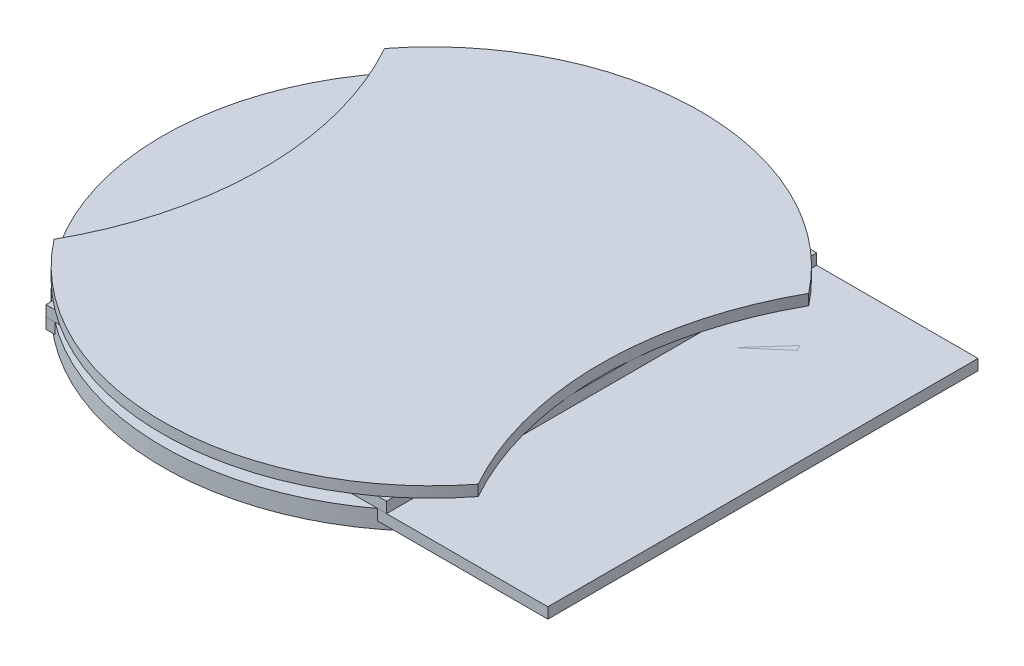
SolidWorks part; units mm, degrees
other "Markup1"
sketch "Sketch33" plane through (-11.66, 9, -138.7946) normal (0, 1, 0) x (1, 0, 0)
other "Markup2"
sketch "Sketch43" plane through (-27.5, 9, 15) normal (-0.0208, 0.9953, 0.0943) x (0.8809, -0.0263, 0.4725)
material "PMMA"
ref_plane "Front Plane" through (0, 0, 0) normal (0, 0, 1) x (1, 0, 0)
ref_plane "Top Plane" through (0, 0, 0) normal (0, 1, 0) x (1, 0, 0)
ref_plane "Right Plane" through (0, 0, 0) normal (1, 0, 0) x (0, 0, -1)
sketch "Sketch1" plane through (0, 0, 0) normal (0, 1, 0) x (1, 0, 0)
  line L1 (0, 0) -> (140, 0)
  line L2 (0, 0) -> (0, 120)
  line L3 (0, 120) -> (140, 120)
  line L4 (140, 0) -> (140, 120)
  dimension "D1" = 120
  dimension "D2" = 140
extrude "Compact" add sketch "Sketch1" along normal blind 3
sketch "Center Guide" plane through (0, 0, 0) normal (-1, 0, 0) x (0, 0, 1)
  line L0 (-60, 0) -> (-60, -3) construction
  line L1 (-120, 0) -> (0, 0) construction
  line L2 (-60, 3) -> (-60, 16.3)
  line L3 (-120, 3) -> (0, 3) construction
  line L4 (-60, 3) -> (-60, 24.5)
  circle A0 centre (-60, -3) radius 10.0584
  circle A1 centre (-60, 16.3) radius 5.9898
  circle A2 centre (-60, 24.5) radius 8.3651
  dimension "D2" = 13.3
  dimension "D3" = 21.5
  dimension "D1" = 3
sketch "Sketch4" plane through (0, 3, 0) normal (0, 1, 0) x (1, 0, 0)
  line L0 (0, 0) -> (140, 0) construction
  line L1 (0, 120) -> (95, 120)
  line L2 (0, 120) -> (0, 0)
  line L3 (0, 0) -> (95, 0)
  line L4 (95, 120) -> (95, 0)
  dimension "D1" = 95
extrude "SuperCompact" add sketch "Sketch4" along normal blind 3 separate body
sketch "Sketch5" plane through (0, 6, 0) normal (0, 1, 0) x (1, 0, 0)
  line L0 (47.5, 120) -> (47.5, 103.0921) construction
  line L1 (95, 120) -> (0, 120) construction
  line L2 (0, 60) -> (21.8037, 60) construction
  line L3 (0, 120) -> (0, 0) construction
  line L4 (70, 120) -> (70, 93.0513) construction
  line L5 (140, 120) -> (0, 120) construction
  circle A0 centre (5, 115) radius 1.5
  circle A1 centre (90, 115) radius 1.5
  circle A2 centre (90, 5) radius 1.5
  circle A3 centre (5, 5) radius 1.5
  circle A4 centre (135, 5) radius 1.5
  circle A5 centre (135, 115) radius 1.5
  dimension "D1" = 3
  dimension "D2" = 5
  dimension "D3" = 5
sketch "Sketch7" plane through (0, 6, 0) normal (0, 1, 0) x (1, 0, 0)
  line L0 (47.5, 120) -> (47.5, 0) construction
  line L1 (95, 120) -> (0, 120) construction
  line L2 (0, 0) -> (95, 0) construction
  circle A0 centre (47.5, 60) radius 75
  dimension "D1" = 150
extrude "Apple Base" add sketch "Sketch7" along normal blind 3 separate body
sketch "Sketch8" plane through (0, 9, 0) normal (0, 1, 0) x (1, 0, 0)
  line L1 (0, 120) -> (0, 0) construction
  line L2 (0, 100.6202) -> (0, 77.7186) construction
  line L3 (47.5, 135) -> (47.5, 108.0988) construction
  line L7 (-27.5, 60) -> (-27.5, 91.6393) construction
  arc A1 (-11.66, 106.0987) -> (-11.66, 13.9013) centre (-94.1268, 60) cw
  circle A2 centre (47.5, 60) radius 75 construction
  circle A3 centre (47.5, 60) radius 75
  arc A4 (-11.66, 106.0987) -> (-11.66, 13.9013) centre (47.5, 60) ccw
  arc A5 (106.66, 106.0987) -> (106.66, 13.9013) centre (189.1268, 60) ccw
  arc A6 (106.66, 106.0987) -> (106.66, 13.9013) centre (47.5, 60) cw
  dimension "D2" = 0
extrude "SideCuts" cut sketch "Sketch8" against normal through all
sketch "Sketch9" plane through (0, 6, 0) normal (0, -1, 0) x (1, 0, 0)
  arc A4 (106.66, -13.9013) -> (-11.66, -13.9013) centre (47.5, -60) ccw
  arc A5 (-11.66, -106.0987) -> (-11.66, -13.9013) centre (-94.1268, -60) ccw
  arc A6 (-11.66, -106.0987) -> (106.66, -106.0987) centre (47.5, -60) ccw
  arc A7 (106.66, -13.9013) -> (106.66, -106.0987) centre (189.1268, -60) ccw
  arc A8 (106.66, -13.9013) -> (-11.66, -13.9013) centre (47.5, -60) ccw
  arc A9 (-11.66, -106.0987) -> (-11.66, -13.9013) centre (-94.1268, -60) ccw
  arc A10 (-11.66, -106.0987) -> (106.66, -106.0987) centre (47.5, -60) ccw
  arc A11 (106.66, -13.9013) -> (106.66, -106.0987) centre (189.1268, -60) ccw
  dimension "D1" = 0
extrude "Apple_Base" add sketch "Sketch9" along normal blind 3 separate body
sketch "Sketch10" plane through (0, 6, 0) normal (0, 1, 0) x (1, 0, 0)
  line L0 (-11.66, 106.0987) -> (-11.66, 13.9013)
  line L1 (106.66, 106.0987) -> (106.66, 13.9013)
  arc A4 (106.66, 106.0987) -> (106.66, 13.9013) centre (189.1268, 60) ccw
  arc A5 (106.66, 106.0987) -> (-11.66, 106.0987) centre (47.5, 60) ccw
  arc A6 (-11.66, 13.9013) -> (-11.66, 106.0987) centre (-94.1268, 60) ccw
  arc A7 (-11.66, 13.9013) -> (106.66, 13.9013) centre (47.5, 60) ccw
  arc A8 (106.66, 106.0987) -> (106.66, 13.9013) centre (189.1268, 60) ccw
  arc A10 (-11.66, 13.9013) -> (-11.66, 106.0987) centre (-94.1268, 60) ccw
  dimension "D1" = 0
extrude "Boss-Extrude4" add sketch "Sketch10" against normal blind 3
sketch "Sketch11" plane through (0, 0, 0) normal (0, 0, 1) x (1, 0, 0)
  line L0 (-11.66, 6) -> (106.66, 6)
  line L1 (47.5, 6) -> (47.5, 18.0317)
fillet "Base_Plate_Fillet" radius 0.001 12 edges at (106.66, 6, -60) (106.66, 3, -60) (-11.66, 6, -60) (-11.66, 3, -60) (47.5, 6, -135) (47.5, 3, -135) (47.5, 6, 15) (47.5, 3, 15) (106.66, 4.5, -106.0987) (-11.66, 4.5, -106.0987) (-11.66, 4.5, -13.9013) (106.66, 4.5, -13.9013)
sketch "Sketch12" plane through (0, 6, 0) normal (0, 1, 0) x (1, 0, 0)
  line L0 (-11.659, 106.0984) -> (-11.659, 13.9016) construction
  line L1 (106.659, 13.9016) -> (106.659, 106.0984) construction
  line L2 (-4.6496, 43.9016) -> (-4.6496, 76.9016) construction
  line L3 (47.5, 134.999) -> (47.5, 105.9694) construction
  circle A0 centre (-4.6496, 43.9016) radius 2.5
  circle A1 centre (-4.6496, 76.9016) radius 2.5
  arc A2 (106.659, 106.0984) -> (-11.659, 106.0984) centre (47.5, 60) ccw construction
  circle A6 centre (99.659, 75.8016) radius 2.5
  circle A7 centre (99.659, 42.8016) radius 2.5
  dimension "D3" = 5
  dimension "D5" = 5
  dimension "D1" = 30
  dimension "D2" = 7.0094
  dimension "D4" = 33
  dimension "D6" = 33
  dimension "D7" = 28.9
  dimension "D8" = 7
extrude "Base_Screw_Holes" [suppressed] cut sketch "Sketch12" against normal blind 14
sketch "Old_Motor_Mounts" plane through (0, 6, 0) normal (0, 1, 0) x (1, 0, 0)
  line L0 (3.341, 134.7458) -> (3.341, -10.3072) construction
  line L1 (47.5, 134.999) -> (47.5, -14.999) construction
  line L2 (-11.659, 106.0984) -> (-11.659, 13.9016) construction
  line L3 (7.341, 70.6984) -> (7.341, 106.6984)
  line L4 (3.341, 70.6984) -> (3.341, 106.6984)
  line L5 (3.341, 106.6984) -> (7.341, 106.6984)
  line L6 (3.341, 70.6984) -> (7.341, 70.6984)
  line L11 (47.5, 60) -> (73.1154, 60) construction
  line L12 (91.659, 49.3016) -> (87.16, 49.4734)
  line L13 (87.16, 49.4734) -> (87.6619, 13.4542)
  line L14 (91.659, 13.3016) -> (87.6619, 13.4542)
  line L15 (91.659, 49.3016) -> (91.659, 13.3016)
  line L16 (106.659, 13.9016) -> (106.659, 106.0984) construction
  arc A0 (106.659, 106.0984) -> (-11.659, 106.0984) centre (47.5, 60) ccw construction
  arc A1 (-11.659, 13.9016) -> (106.659, 13.9016) centre (47.5, 60) ccw construction
  point P12 (3.341, 88.6984)
  point P16 (91.659, 31.3016)
  dimension "D1" = 15
  dimension "D2" = 17.4
  dimension "D3" = 36
  dimension "D5" = 36
  dimension "D6" = 15
  dimension "D7" = 4
  dimension "D8" = 17.4
  dimension "D4" = 4
ref_plane "MidPlane" through (0, 0, -60) normal (0, 0, 1) x (1, 0, 0)
sketch "Sketch24" plane through (0, 6, 0) normal (0, 1, 0) x (1, 0, 0)
  line L0 (-3.66, 114.8421) -> (-3.66, 5.1579)
  line L2 (-11.66, 13.9016) -> (-11.66, 106.0984) construction
  line L3 (47.5, 134.999) -> (47.5, 105.1076) construction
  line L4 (98.66, 114.8421) -> (98.66, 5.1579)
  line L5 (106.66, 106.0984) -> (106.66, 13.9016) construction
  line L6 (106.66, 106.0984) -> (106.66, 13.9016)
  line L7 (-11.66, 13.9016) -> (-11.66, 106.0984)
  arc A0 (106.659, 106.0984) -> (-11.659, 106.0984) centre (47.5, 60) ccw construction
  arc A1 (-11.6598, 106.099) -> (-11.66, 106.0984) centre (-11.659, 106.0984) ccw construction
  arc A2 (106.6598, 106.099) -> (-11.6598, 106.099) centre (47.5, 60) ccw construction
  arc A3 (106.66, 106.0984) -> (106.6598, 106.099) centre (106.659, 106.0984) ccw construction
  arc A4 (106.6598, 13.901) -> (106.66, 13.9016) centre (106.659, 13.9016) ccw construction
  arc A5 (-11.6598, 13.901) -> (106.6598, 13.901) centre (47.5, 60) ccw construction
  arc A6 (-11.66, 13.9016) -> (-11.6598, 13.901) centre (-11.659, 13.9016) ccw construction
  arc A7 (-11.6598, 106.099) -> (-11.66, 106.0984) centre (-11.659, 106.0984) ccw
  arc A8 (106.6598, 106.099) -> (98.66, 114.8421) centre (47.5, 60) ccw
  arc A9 (106.66, 106.0984) -> (106.6598, 106.099) centre (106.659, 106.0984) ccw
  arc A10 (106.6598, 13.901) -> (106.66, 13.9016) centre (106.659, 13.9016) ccw
  arc A11 (-11.6598, 13.901) -> (-3.66, 5.1579) centre (47.5, 60) ccw
  arc A12 (-11.66, 13.9016) -> (-11.6598, 13.901) centre (-11.659, 13.9016) ccw
  arc A13 (98.66, 5.1579) -> (106.6598, 13.901) centre (47.5, 60) ccw
  arc A14 (-3.66, 114.8421) -> (-11.6598, 106.099) centre (47.5, 60) ccw
  dimension "D1" = 8
  dimension "D2" = 8
extrude "Cut-Extrude3" [suppressed] cut sketch "Sketch24" against normal blind 6
sketch "Sketch25" plane through (0, 6, 0) normal (0, 1, 0) x (1, 0, 0)
  line L0 (-11.659, 106.0974) -> (-11.659, 111.0974)
  line L1 (47.5, 135) -> (47.5, 124.3332) construction
  line L2 (106.659, 106.0974) -> (106.659, 111.0974)
  line L3 (-11.66, 60) -> (55.4784, 60) construction
  line L4 (-11.66, 13.9016) -> (-11.66, 106.0984) construction
  line L5 (106.659, 13.9026) -> (106.659, 8.9026)
  line L6 (-11.659, 13.9026) -> (-11.659, 8.9026)
  arc A0 (-11.6598, 106.099) -> (-11.66, 106.0984) centre (-11.659, 106.0984) ccw construction
  arc A1 (106.6598, 106.099) -> (-11.6598, 106.099) centre (47.5, 60) ccw construction
  arc A2 (-11.659, 111.0974) -> (106.659, 111.0974) centre (47.5, 61.7666) cw
  arc A3 (-11.659, 106.0974) -> (106.659, 106.0974) centre (47.5, 56.7666) cw
  arc A4 (-11.659, 13.9026) -> (106.659, 13.9026) centre (47.5, 63.2334) ccw
  arc A5 (-11.659, 8.9026) -> (106.659, 8.9026) centre (47.5, 58.2334) ccw
  arc M15 (106.659, 106.0984) -> (-11.659, 106.0984) centre (47.5, 60) ccw
  arc M17 (-11.659, 13.9016) -> (106.659, 13.9016) centre (47.5, 60) ccw
  dimension "D1" = 5
extrude "Top Bottom extensions" add sketch "Sketch25" against normal blind 3 contours L6 A5 L5 A4 M17 | L0 A3 L2 A2 M15
sketch "Sketch28" plane through (0, 6, 0) normal (0, 1, 0) x (1, 0, 0)
  line L0 (-11.659, 60) -> (106.659, 60) construction
  line L1 (37.5, 6) -> (57.5, 6) construction
  line L2 (37.5, 6) -> (37.5, -14) construction
  line L3 (37.5, -14) -> (57.5, -14) construction
  line L4 (57.5, 6) -> (57.5, -14) construction
  line L5 (-11.659, 106.0984) -> (-11.659, 13.9016) construction
  line L6 (106.659, 13.9016) -> (106.659, 106.0984) construction
  line L7 (47.5, 6) -> (47.5, -4) construction
  line L8 (47.5, -4) -> (37.5, -4) construction
  circle A0 centre (41.5, 2) radius 1.75
  circle A1 centre (41.5, -10) radius 1.75
  circle A2 centre (53.5, -10) radius 1.75
  circle A3 centre (53.5, 2) radius 1.75
  circle A4 centre (53.5, 130) radius 1.75
  circle A5 centre (53.5, 118) radius 1.75
  circle A6 centre (41.5, 118) radius 1.75
  circle A7 centre (41.5, 130) radius 1.75
  point P30 (47.5, 60)
  dimension "D4" = 3.5
  dimension "D1" = 20
  dimension "D2" = 20
  dimension "D3" = 54
  dimension "D5" = 4
  dimension "D6" = 4
extrude "RodHolder holes" [suppressed] cut sketch "Sketch28" against normal blind 11
sketch "Sketch29" plane through (0, 6, 0) normal (0, 1, 0) x (1, 0, 0)
  line L0 (47.5, 138.7946) -> (47.5, -18.7946) construction
  line L5 (47.5, 60) -> (59.8359, 60) construction
  line L7 (11.25, 7.85) -> (83.75, 7.85) construction
  line L8 (11.25, 7.85) -> (11.25, 112.15) construction
  line L9 (11.25, 112.15) -> (83.75, 112.15) construction
  line L10 (83.75, 7.85) -> (83.75, 112.15) construction
  line L11 (11.25, 7.85) -> (83.75, 112.15) construction
  line L12 (11.25, 112.15) -> (83.75, 7.85) construction
  arc A5 (106.659, 111.0974) -> (-11.659, 111.0974) centre (47.5, 61.7666) ccw construction
  arc A6 (-11.659, 8.9026) -> (106.659, 8.9026) centre (47.5, 58.2334) ccw construction
  circle A7 centre (11.25, 112.15) radius 1.5
  circle A8 centre (83.75, 112.15) radius 1.5
  circle A9 centre (83.75, 7.85) radius 1.5
  circle A10 centre (11.25, 7.85) radius 1.5
  point P9 (47.5, 60)
  dimension "D1" = 104.3
  dimension "D3" = 3
  dimension "D2" = 72.5
extrude "Height extender holes" [suppressed] cut sketch "Sketch29" against normal blind 10
sketch "Sketch31" plane through (0, 6, 0) normal (0, 1, 0) x (1, 0, 0)
  line L0 (-11.659, 60) -> (106.659, 60) construction
  line L1 (-11.659, 106.0984) -> (-11.659, 13.9016) construction
  line L2 (106.659, 13.9016) -> (106.659, 106.0984) construction
  line L3 (47.5, 138.7946) -> (47.5, -18.7946) construction
  line L4 (47.5, 112) -> (72.8768, 112) construction
  arc A0 (106.659, 111.0974) -> (-11.659, 111.0974) centre (47.5, 61.7666) ccw construction
  arc A1 (-11.659, 8.9026) -> (106.659, 8.9026) centre (47.5, 58.2334) ccw construction
  circle A2 centre (47.5, 122) radius 10
  circle A3 centre (47.5, 122) radius 8
  circle A4 centre (47.5, 122) radius 15
  dimension "D1" = 20
  dimension "D3" = 2
  dimension "D4" = 30
  dimension "D2" = 52
sketch "Sketch34" plane through (0, 3, 0) normal (0, -1, 0) x (-1, 0, 0)
  line L0 (-47.5, -18.7946) -> (-47.5, 138.7946) construction
  arc A0 (-106.659, 8.9026) -> (11.659, 8.9026) centre (-47.5, 58.2334) ccw construction
  arc A1 (11.659, 111.0974) -> (-106.659, 111.0974) centre (-47.5, 61.7666) ccw construction
  circle A2 centre (-47.5, 60) radius 12.859
sketch "Sketch35" plane through (0, 3, 0) normal (0, -1, 0) x (1, 0, 0)
  line L0 (47.5, 18.7946) -> (47.5, -138.7946) construction
  line L1 (6.25, -114.85) -> (88.75, -114.85) construction
  line L2 (47.5, -60) -> (61.5955, -60) construction
  line L3 (7.5, -3.9) -> (7.5, -116.1) construction
  line L4 (6.25, -5.15) -> (86.25, -5.15) construction
  line L5 (87.5, -3.9) -> (87.5, -116.1) construction
  line L6 (7.5, 18.7946) -> (7.5, -138.7946) construction
  line L7 (87.5, 18.7946) -> (87.5, -138.7946) construction
  arc A0 (106.659, -8.9026) -> (-11.659, -8.9026) centre (47.5, -58.2334) ccw construction
  arc A1 (-11.659, -111.0974) -> (106.659, -111.0974) centre (47.5, -61.7666) ccw construction
  circle A2 centre (7.5, -5.15) radius 1.25
  circle A3 centre (87.5, -5.15) radius 1.25
  circle A4 centre (87.5, -114.85) radius 1.25
  circle A5 centre (7.5, -114.85) radius 1.25
  dimension "D1" = 40
  dimension "D3" = 2.5
  dimension "D4" = 80
  dimension "D5" = 112.2
  dimension "D2" = 40
extrude "SpacerHoles" cut sketch "Sketch35" against normal blind 10
sketch "Sketch37" plane through (0, 3, 0) normal (0, -1, 0) x (1, 0, 0)
sketch "Sketch38" plane through (0, 3, 0) normal (0, -1, 0) x (1, 0, 0)
  line L0 (-11.659, -60) -> (-6.659, -60)
  line L1 (-11.659, -13.9016) -> (-11.659, -106.0984) construction
  line L2 (-6.659, -60) -> (-6.659, 24.7024)
  line L3 (101.659, -60) -> (106.659, -60)
  line L4 (106.659, -106.0984) -> (106.659, -13.9016) construction
  line L5 (-6.659, 24.7024) -> (101.659, 24.7024)
  line L6 (101.659, 24.7024) -> (101.659, -143.8435)
  line L7 (101.659, -143.8435) -> (-6.659, -143.8435)
  line L8 (-6.659, -143.8435) -> (-6.659, -60)
  line L9 (47.5, 37.0501) -> (120.3723, 37.0501)
  line L10 (120.3723, 37.0501) -> (120.3723, -158.6018)
  line L11 (120.3723, -158.6018) -> (-29.1775, -158.6018)
  line L12 (-29.1775, -158.6018) -> (-29.1775, 37.0501)
  line L13 (-29.1775, 37.0501) -> (47.5, 37.0501)
  line M7 (106.659, -106.0984) -> (106.659, -13.9016)
  line M8 (106.659, -13.9016) -> (106.659, -8.9026)
  arc M9 (106.659, -8.9026) -> (-11.659, -8.9026) centre (47.5, -58.2334) ccw
  line M10 (-11.659, -8.9026) -> (-11.659, -13.9016)
  line M11 (-11.659, -13.9016) -> (-11.659, -106.0984)
  line M12 (-11.659, -106.0984) -> (-11.659, -111.0974)
  arc M13 (-11.659, -111.0974) -> (106.659, -111.0974) centre (47.5, -61.7666) ccw
  line M14 (106.659, -111.0974) -> (106.659, -106.0984)
  dimension "D1" = 5
  dimension "D2" = 5
extrude "Cut-Extrude4" cut sketch "Sketch38" against normal blind 10 contours L13 L12 L11 L10 L9 L7 L8 L2 L5 L6 M13 M12 M11 M10 M9 M8 M7 M14 | L6 L3 M9 M7 M8 | L0 L2 M9 M10 M11 | L8 L0 M13 M11 M12 | L3 L6 M13 M14 M7
sketch "Sketch39" plane through (0, 3, 0) normal (0, -1, 0) x (1, 0, 0)
  line L0 (47.5, 18.7946) -> (47.5, -81.8228) construction
  line L2 (101.659, -60) -> (38.5892, -60) construction
  line L3 (101.659, -3.4601) -> (101.659, -116.5399) construction
  arc A1 (101.659, -3.4601) -> (-6.659, -3.4601) centre (47.5, -58.2334) ccw construction
  circle A2 centre (47.5, -60) radius 75
  circle A3 centre (87.5, -5.15) radius 1.25
  circle A4 centre (7.5, -5.15) radius 1.25
  circle A5 centre (7.5, -114.85) radius 1.25
  circle A6 centre (87.5, -114.85) radius 1.25
  dimension "D1" = 150
extrude "Boss-Extrude5" add sketch "Sketch39" along normal blind 5
sketch "Sketch40" plane through (101.659, 0, 0) normal (1, 0, 0) x (0, 0, -1)
  line L0 (3.4601, 3) -> (-22.7338, 3)
  line L1 (-22.7338, 3) -> (-22.7338, 8.214)
  line L2 (-22.7338, 8.214) -> (147.503, 8.214)
  line L3 (147.503, 8.214) -> (147.503, 3)
  line L4 (147.503, 3) -> (3.4601, 3)
extrude "Cut-Extrude5" cut sketch "Sketch40" against normal blind 150
sketch "Sketch41" plane through (0, 3, 0) normal (0, 1, 0) x (1, 0, 0)
  line L0 (47.5, 60) -> (79.7, 60)
  line L1 (79.7, 60) -> (111.9, 60)
  circle A3 centre (47.5, 60) radius 8.5
  circle A4 centre (79.7, 60) radius 8.5
  circle A5 centre (111.9, 60) radius 8.5
  dimension "D2" = 32.2
  dimension "D5" = 17
  dimension "D6" = 17
  dimension "D4" = 17
  dimension "D3" = 32.2
extrude "Cut-Extrude6" cut sketch "Sketch41" against normal blind 10
sketch "Sketch44" plane through (0, 3, 0) normal (0, 1, 0) x (1, 0, 0)
  line L0 (79.7, 60) -> (111.7, 60)
  circle A0 centre (111.7, 60) radius 8.5
  dimension "D2" = 17
  dimension "D1" = 32
extrude "Cut-Extrude7" cut sketch "Sketch44" against normal blind 10
